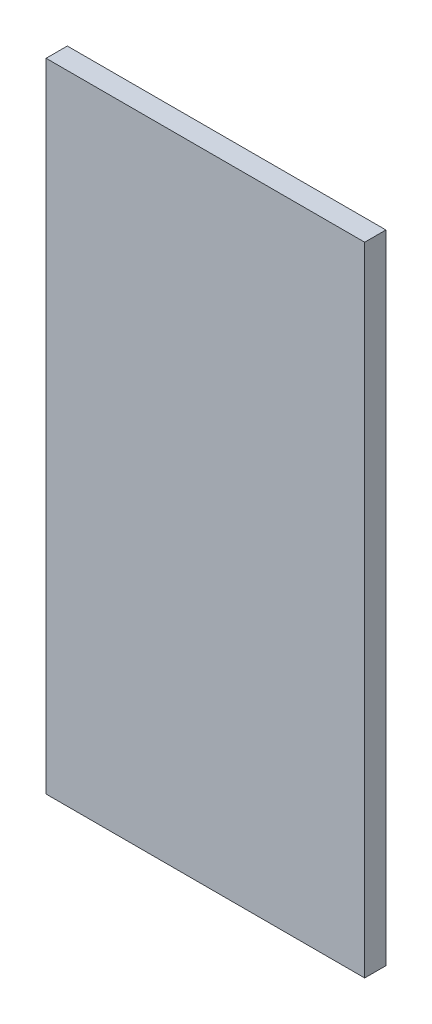
SolidWorks part; units mm, degrees
ref_plane "Alzado" through (0, 0, 0) normal (0, 0, 1) x (1, 0, 0)
ref_plane "Planta" through (0, 0, 0) normal (0, 1, 0) x (1, 0, 0)
ref_plane "Vista lateral" through (0, 0, 0) normal (1, 0, 0) x (0, 0, -1)
ref_plane "Plano1" through (0, 0, 360) normal (0, 0, -1) x (-1, 0, 0)
sketch "Croquis1" plane through (0, 0, 360) normal (0, 0, -1) x (-1, 0, 0)
  line L0 (7.7541, -142.1656) -> (7.7541, -132.1656) construction
  line L1 (-152.2459, -142.1656) -> (167.7541, -142.1656) construction
  line L2 (-152.2459, 177.8344) -> (167.7541, 177.8344) construction
  line L3 (7.7541, 167.8344) -> (7.7541, 177.8344) construction
  line L4 (-67.2459, 167.8344) -> (82.7541, 167.8344)
  line L5 (-67.2459, 167.8344) -> (-67.2459, -132.1656)
  line L6 (-67.2459, -132.1656) -> (82.7541, -132.1656)
  line L7 (82.7541, 167.8344) -> (82.7541, -132.1656)
  point P6 (7.7541, 12.1668)
  dimension "D1" = 150
  dimension "D2" = 300
extrude "Saliente-Extruir1" add sketch "Croquis1" along normal blind 10
